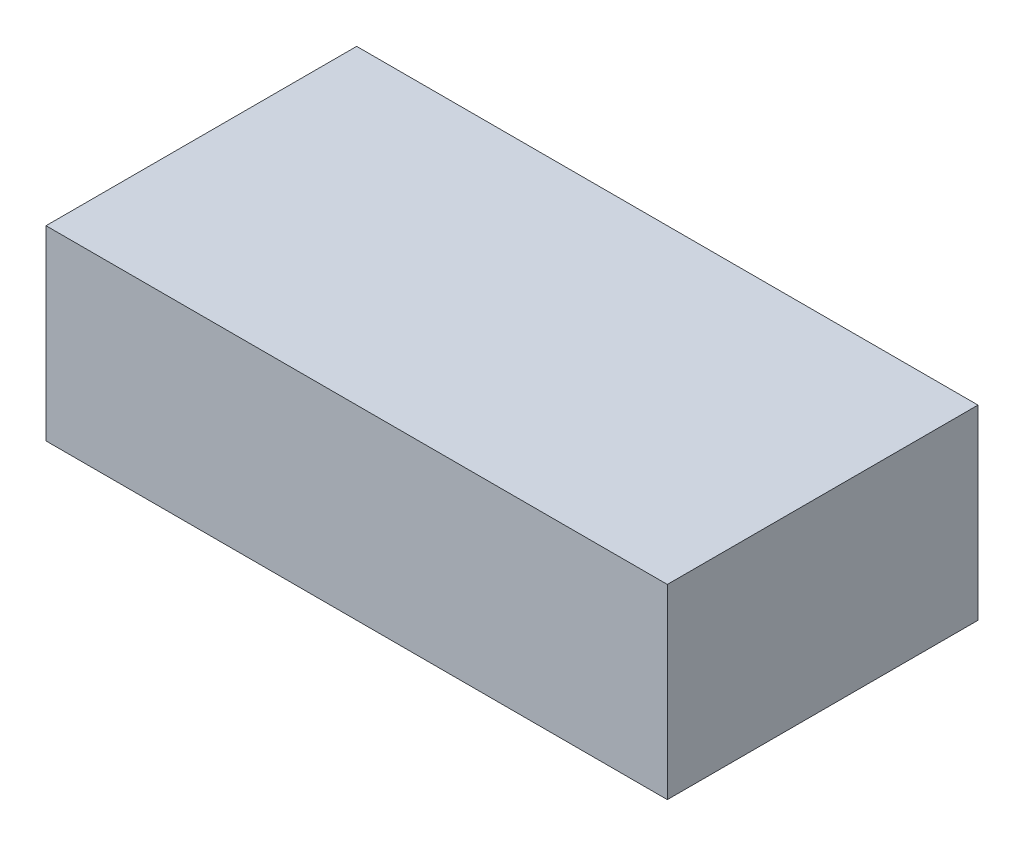
SolidWorks part; units mm, degrees
ref_plane "Front Plane" through (0, 0, 0) normal (0, 0, 1) x (1, 0, 0)
ref_plane "Top Plane" through (0, 0, 0) normal (0, 1, 0) x (1, 0, 0)
ref_plane "Right Plane" through (0, 0, 0) normal (1, 0, 0) x (0, 0, -1)
sketch "Sketch1" plane through (0, 0, 0) normal (0, 1, 0) x (1, 0, 0)
  line L1 (0, 0) -> (100, 0)
  line L2 (0, 0) -> (0, 50)
  line L3 (0, 50) -> (100, 50)
  line L4 (100, 0) -> (100, 50)
  dimension "D1" = 100
  dimension "D2" = 50
extrude "Boss-Extrude1" add sketch "Sketch1" along normal blind 30
